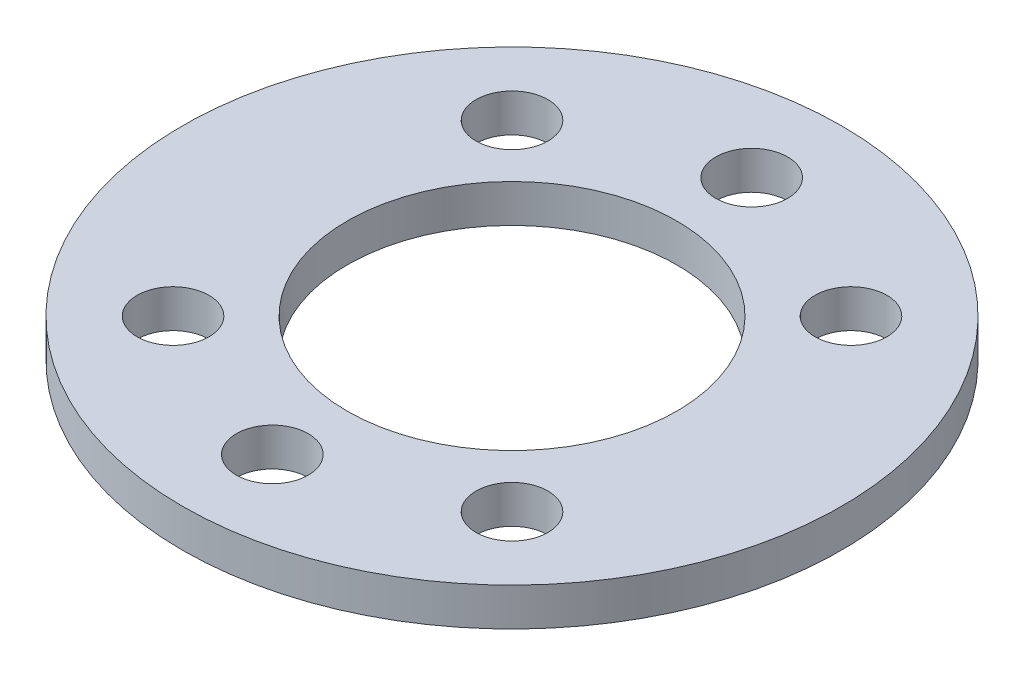
SolidWorks part; units mm, degrees
ref_plane "Front Plane" through (0, 0, 0) normal (0, 0, 1) x (1, 0, 0)
ref_plane "Top Plane" through (0, 0, 0) normal (0, 1, 0) x (1, 0, 0)
ref_plane "Right Plane" through (0, 0, 0) normal (1, 0, 0) x (0, 0, -1)
sketch "Sketch1" plane through (0, 0, 0) normal (0, 1, 0) x (1, 0, 0)
  circle A0 centre (0, 0) radius 22
  circle A1 centre (0, 0) radius 11
  dimension "D1" = 44
  dimension "D2" = 22
extrude "Boss-Extrude1" add sketch "Sketch1" along normal blind 2.54 contours A0 A1
sketch "Sketch2" plane through (0, 2.54, 0) normal (0, 1, 0) x (1, 0, 0)
  circle A0 centre (0, 0) radius 16
  circle A1 centre (0, 16) radius 2.4
  circle A2 centre (-11.3137, 11.3137) radius 2.4
  circle A3 centre (11.3137, 11.3137) radius 2.4
  circle A4 centre (11.3137, -11.3137) radius 2.4
  circle A5 centre (0, -16) radius 2.4
  circle A6 centre (-11.3137, -11.3137) radius 2.4
  point P18 (0, 0)
  dimension "D1" = 32
  dimension "D2" = 4.8
  dimension "D3" = 45
  dimension "D4" = 45
  dimension "D5" = 2
extrude "Cut-Extrude1" cut sketch "Sketch2" against normal blind 10 contours A2 | A1 | A3 | A4 | A5 | A6
